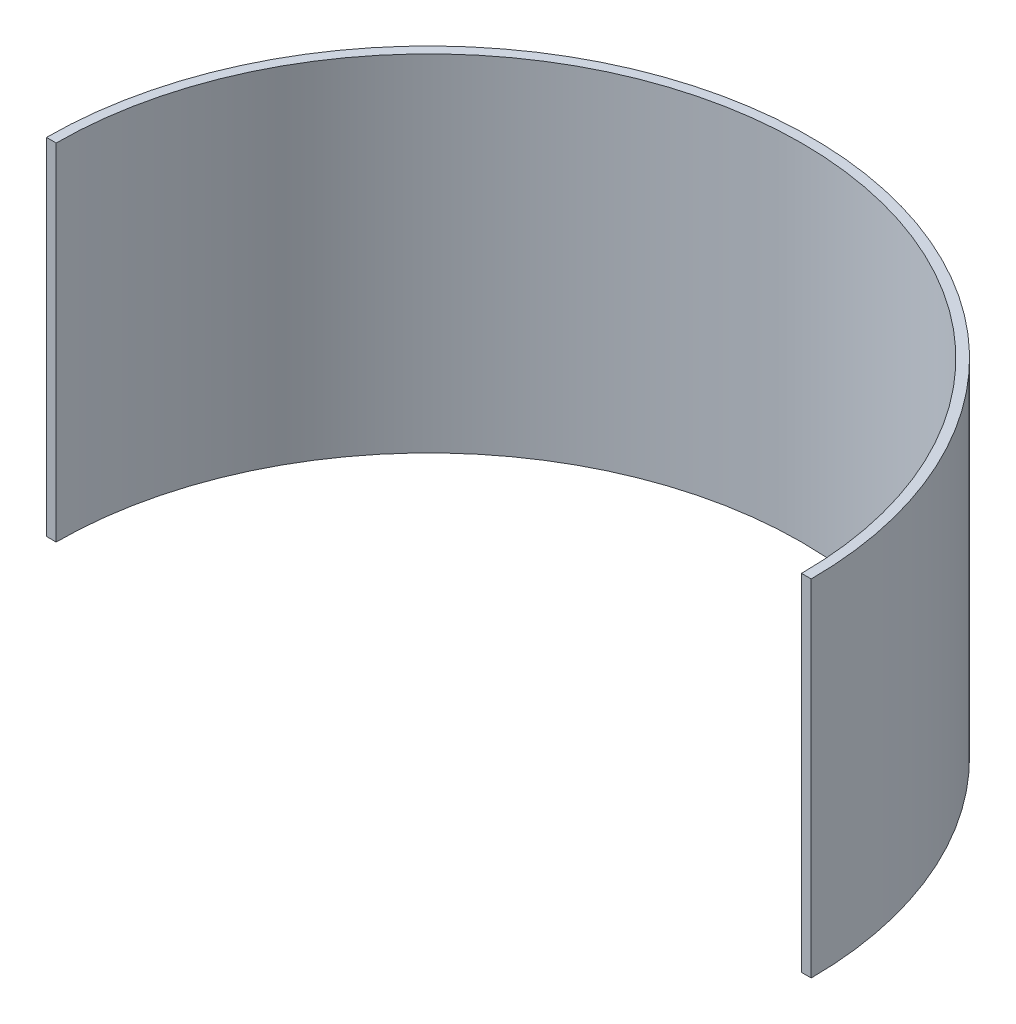
SolidWorks part; units mm, degrees
ref_plane "Front Plane" through (0, 0, 0) normal (0, 0, 1) x (1, 0, 0)
ref_plane "Top Plane" through (0, 0, 0) normal (0, 1, 0) x (1, 0, 0)
ref_plane "Right Plane" through (0, 0, 0) normal (1, 0, 0) x (0, 0, -1)
sketch "Sketch1" plane through (0, 0, 0) normal (0, 1, 0) x (1, 0, 0)
  line L0 (-27.55, 0) -> (27.55, 0)
  circle A0 centre (0, 0) radius 27.55
  circle A1 centre (0, 0) radius 26.852
  dimension "D1" = 55.1
  dimension "D2" = 53.704
extrude "Boss-Extrude1" add sketch "Sketch1" along normal blind 24.9 contours A1 L0 A0
